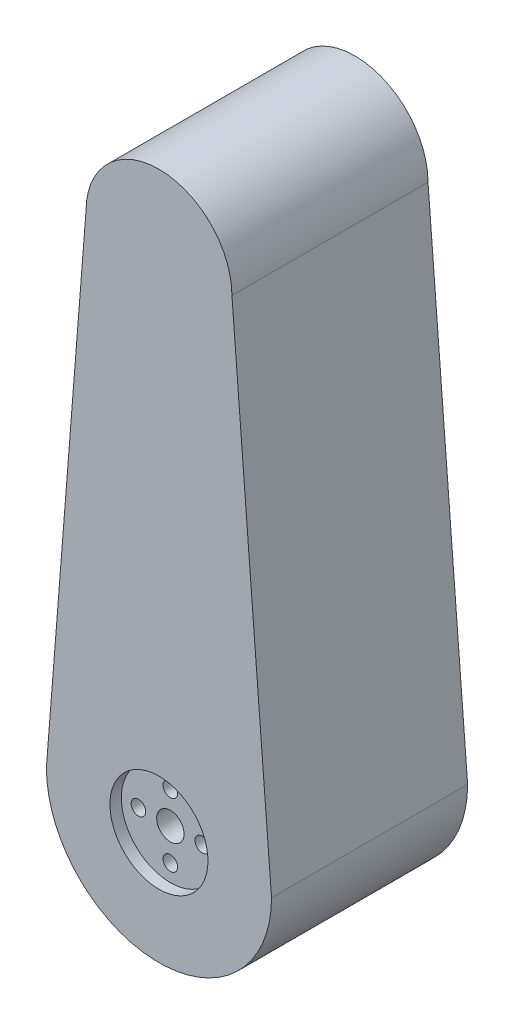
SolidWorks part; units mm, degrees
ref_plane "Front Plane" through (0, 0, 0) normal (0, 0, 1) x (1, 0, 0)
ref_plane "Top Plane" through (0, 0, 0) normal (0, 1, 0) x (1, 0, 0)
ref_plane "Right Plane" through (0, 0, 0) normal (1, 0, 0) x (0, 0, -1)
sketch "Sketch1" plane through (0, 0, 0) normal (0, 0, 1) x (1, 0, 0)
  line L1 (16, 110) -> (24.6859, 0)
  line L2 (-24.6859, 0) -> (-16, 110)
  arc A0 (-24.6859, 0) -> (24.6859, 0) centre (0, 0) ccw
  arc A1 (16, 110) -> (-16, 110) centre (0, 110) ccw
extrude "Boss-Extrude1" add sketch "Sketch1" along normal mid plane 43
sketch "Sketch2" plane through (0, 0, 21.5) normal (0, 0, 1) x (1, 0, 0)
  circle A0 centre (0, 0) radius 10.75
extrude "Cut-Extrude1" cut sketch "Sketch2" against normal blind 2.5
sketch "Sketch3" plane through (0, 0, 19) normal (0, 0, 1) x (1, 0, 0)
  circle A0 centre (0, 0) radius 3
  circle A2 centre (0, 7) radius 1.6
  circle A3 centre (7, 0) radius 1.6
  circle A4 centre (0, -7) radius 1.6
  circle A5 centre (-7, 0) radius 1.6
  point P14 (0, 0)
  dimension "D1" = 4
extrude "Cut-Extrude2" cut sketch "Sketch3" against normal blind 10
sketch "Sketch4" plane through (0, 0, -21.5) normal (0, 0, -1) x (-1, 0, 0)
  circle A0 centre (0, 0) radius 4
extrude "Boss-Extrude2" add sketch "Sketch4" along normal blind 6
sketch "Sketch6" plane through (0, 0, -21.5) normal (0, 0, -1) x (-1, 0, 0)
  line L7 (6.4, 116) -> (-6.4, 116)
  line L8 (-6.4, 116) -> (-6.4, 92.5)
  line L9 (-6.4, 92.5) -> (6.4, 92.5)
  line L10 (6.4, 116) -> (6.4, 92.5)
extrude "Cut-Extrude3" cut sketch "Sketch6" against normal blind 18
sketch "Sketch8" plane through (0, 0, -21.5) normal (0, 0, -1) x (-1, 0, 0)
  circle A0 centre (0, 118.6) radius 1
  circle A1 centre (0, 89.9) radius 1
  dimension "D2" = 2
  dimension "D3" = 2
extrude "Cut-Extrude4" cut sketch "Sketch8" against normal blind 8
